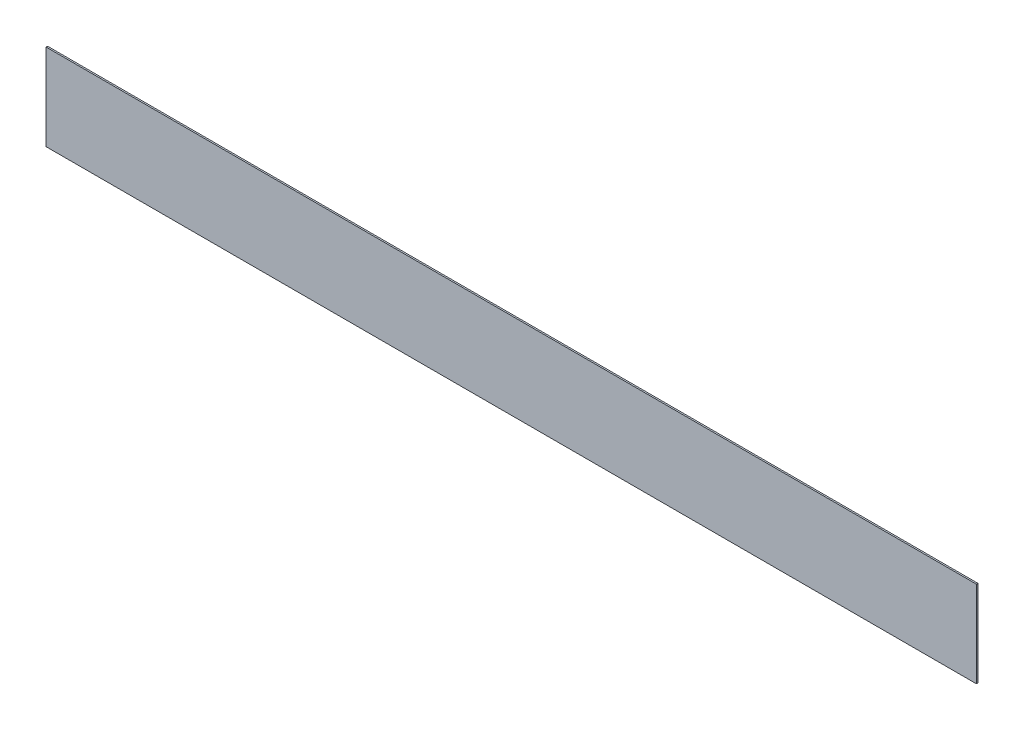
SolidWorks part; units mm, degrees
ref_plane "Front Plane" through (0, 0, 0) normal (0, 0, 1) x (1, 0, 0)
ref_plane "Top Plane" through (0, 0, 0) normal (0, 1, 0) x (1, 0, 0)
ref_plane "Right Plane" through (0, 0, 0) normal (1, 0, 0) x (0, 0, -1)
sketch "Sketch1" plane through (0, 0, 0) normal (0, 0, 1) x (1, 0, 0)
  line L0 (1240, 115) -> (1240, 0)
  line L1 (1240, 115) -> (0, 115)
  line L2 (1240, 0) -> (0, 0)
  line L3 (0, 115) -> (0, 0)
other "Pen Sketch1" parameters "D1"=69.7562, "D2"=44.2015
extrude "Boss-Extrude1" add sketch "Sketch1" along normal blind 2
